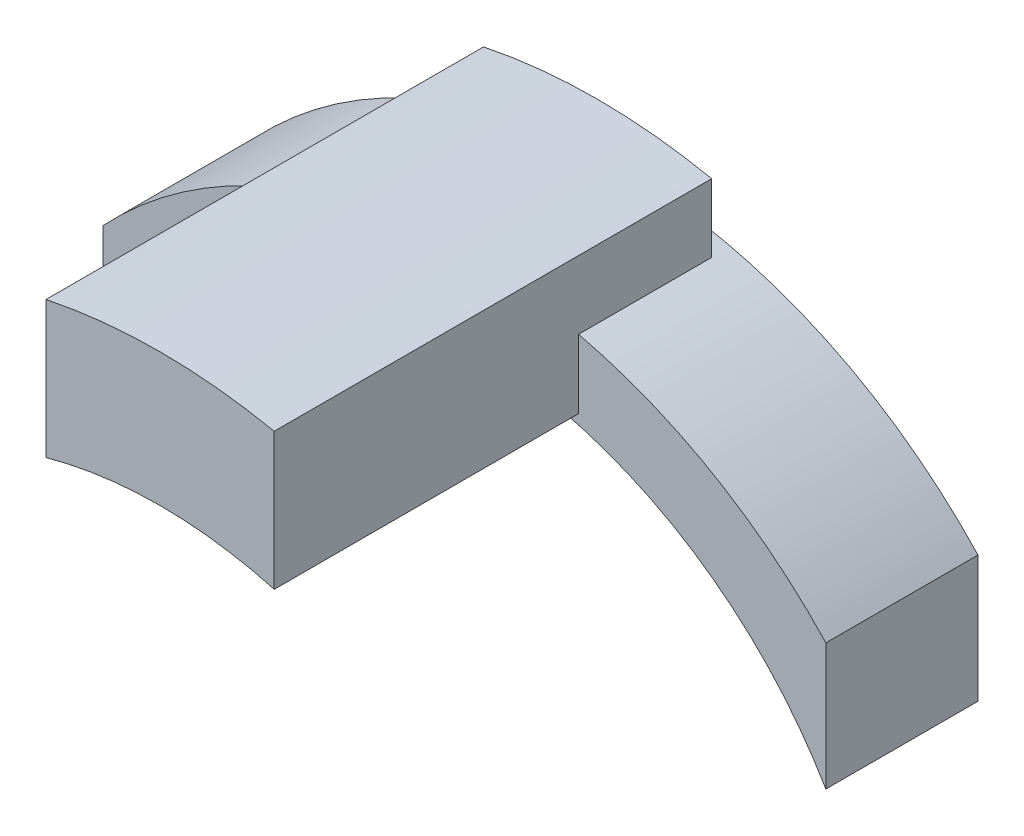
SolidWorks part; units mm, degrees
ref_plane "Front Plane" through (0, 0, 0) normal (0, 0, 1) x (1, 0, 0)
ref_plane "Top Plane" through (0, 0, 0) normal (0, 1, 0) x (1, 0, 0)
ref_plane "Right Plane" through (0, 0, 0) normal (1, 0, 0) x (0, 0, -1)
sketch "Sketch1" plane through (0, 0, 0) normal (0, 0, 1) x (1, 0, 0)
  line L0 (-19, 11.0905) -> (-19, 17.7482)
  line L1 (19, 17.7482) -> (19, 11.0905)
  arc A0 (19, 11.0905) -> (-19, 11.0905) centre (0, 0) ccw
  arc A1 (19, 17.7482) -> (-19, 17.7482) centre (0, 0) ccw
  dimension "D1" = 44
  dimension "D3" = 4
  dimension "D2" = 38
extrude "Extrude1" add sketch "Sketch1" along normal mid plane 8
sketch "Sketch2" plane through (0, 0, 4) normal (0, 0, -1) x (-1, 0, 0)
  line L0 (6, 21.6852) -> (6, 28.8834)
  line L1 (-6, 28.8834) -> (-6, 21.6852)
  arc A0 (6, 28.8834) -> (-6, 28.8834) centre (0, 0) ccw
  arc A2 (6, 21.6852) -> (-6, 21.6852) centre (0, 0) ccw
  arc A3 (19, 11.0905) -> (-19, 11.0905) centre (0, 0) ccw construction
  dimension "D2" = 7
  dimension "D3" = 0.5
  dimension "D1" = 12
extrude "Extrude2" add sketch "Sketch2" against normal blind 16 and the other way blind 7
